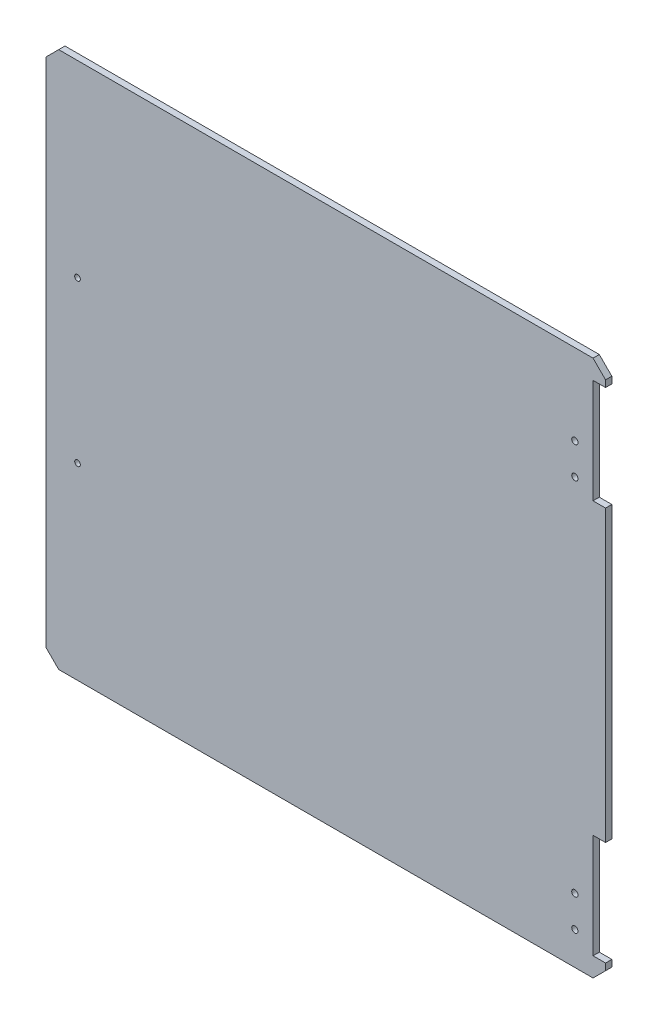
SolidWorks part; units mm, degrees
material "ABS PC"
ref_plane "Piano frontale" through (0, 0, 0) normal (0, 0, 1) x (1, 0, 0)
ref_plane "Piano superiore" through (0, 0, 0) normal (0, 1, 0) x (1, 0, 0)
ref_plane "Piano destro" through (0, 0, 0) normal (1, 0, 0) x (0, 0, -1)
sketch "Schizzo1" plane through (0, 0, 0) normal (0, 0, 1) x (1, 0, 0)
  line L0 (-223, 204) -> (-213, 214)
  line L1 (213, -214) -> (-213, -214)
  line L2 (223, -115.4707) -> (223, 115.4707)
  line L3 (213, 214) -> (-213, 214)
  line L4 (-223, -204) -> (-223, 204)
  line L5 (223, -214) -> (-223, 214) construction
  line L6 (223, 214) -> (-223, -214) construction
  line L7 (223, 204) -> (213, 214)
  line L8 (213, -214) -> (223, -204)
  line L9 (-213, -214) -> (-223, -204)
  line L10 (223, -198.6584) -> (213, -198.6584)
  line L11 (-223, 0) -> (221, 0) construction
  line L12 (213, -198.6584) -> (213, -115.4707)
  line L13 (213, -115.4707) -> (223, -115.4707)
  line L14 (223, -204) -> (223, -198.6584)
  line L15 (223, 198.6584) -> (213, 198.6584)
  line L16 (213, 198.6584) -> (213, 115.4707)
  line L17 (213, 115.4707) -> (223, 115.4707)
  line L18 (223, 198.6584) -> (223, 204)
  circle A0 centre (198.518, 149.6524) radius 2.5
  circle A1 centre (198.518, 124.6524) radius 2.5
  circle A2 centre (198.4941, -162.7476) radius 2.4991
  circle A3 centre (198.518, -187.7476) radius 2.4991
  circle A5 centre (-198, 64) radius 2.25
  circle A6 centre (-198, -64) radius 2.25
  point P0 (0, 0)
  dimension "D12" = 4.5
  dimension "D1" = 446
  dimension "D2" = 428
  dimension "D3" = 25
  dimension "D4" = 25
  dimension "D10" = 25
  dimension "D11" = 64
extrude "Estrusione-Estrusione1" add sketch "Schizzo1" along normal blind 5
